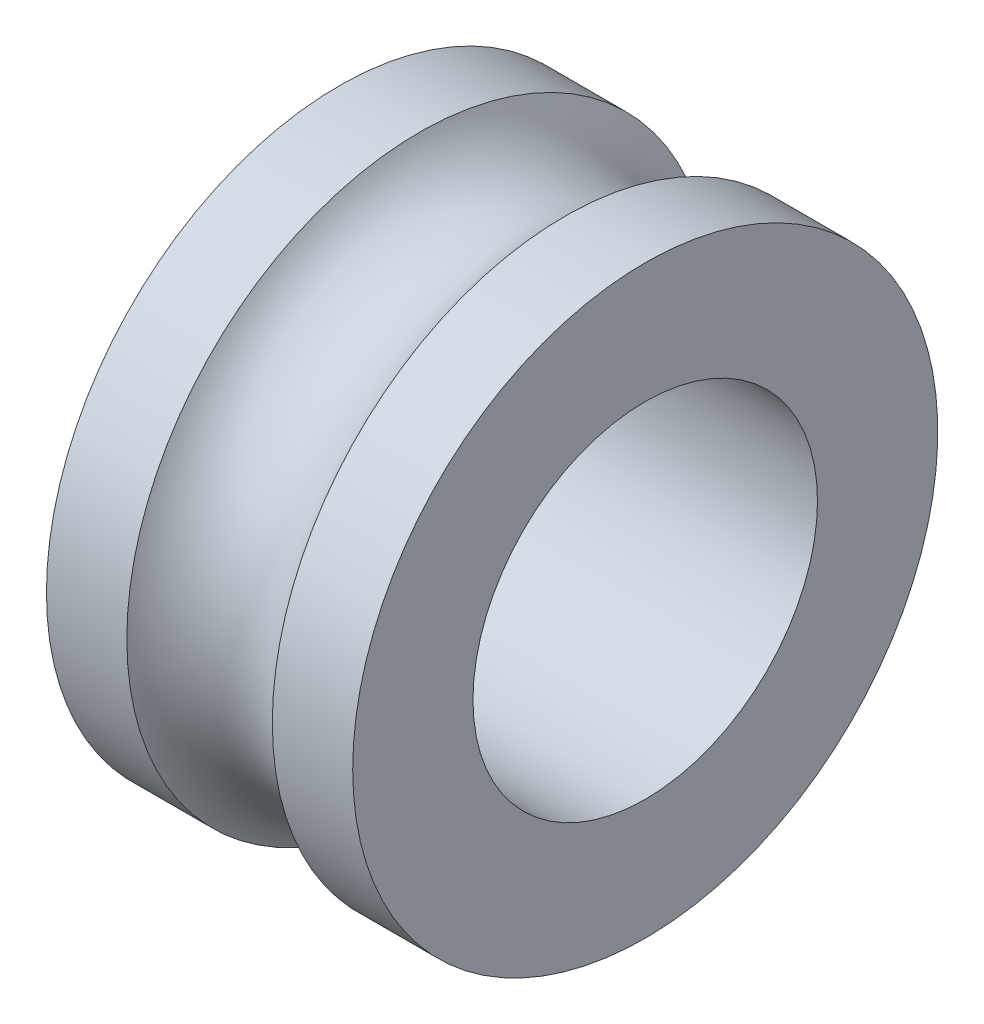
SolidWorks part; units mm, degrees
ref_plane "Front Plane" through (0, 0, 0) normal (0, 0, 1) x (1, 0, 0)
ref_plane "Top Plane" through (0, 0, 0) normal (0, 1, 0) x (1, 0, 0)
ref_plane "Right Plane" through (0, 0, 0) normal (1, 0, 0) x (0, 0, -1)
sketch "Sketch1" plane through (0, 0, 0) normal (0, 0, 1) x (1, 0, 0)
  line L0 (0, 0) -> (4, 0)
  line L1 (0, 0) -> (-4, 0)
  line L2 (-4, 0) -> (-4, 3.142)
  line L3 (4, 0) -> (4, 3.142)
  line L4 (-4, 3.142) -> (-1.9, 3.142)
  line L5 (4, 3.142) -> (1.9, 3.142)
  line L6 (-1.9, 3.142) -> (1.9, 3.142) construction
  line L7 (-4, 3.142) -> (-4, -4.5) construction
  line L8 (-4, -4.5) -> (4, -4.5) construction
  arc A0 (-1.9, 3.142) -> (1.9, 3.142) centre (0, 4.2511) ccw
  dimension "D6" = 2.2
  dimension "D1" = 4
  dimension "D2" = 4
  dimension "D3" = 3.142
  dimension "D4" = 2.1
  dimension "D5" = 7.642
revolve "Revolve1" add sketch "Sketch1" angle 360 about L8
